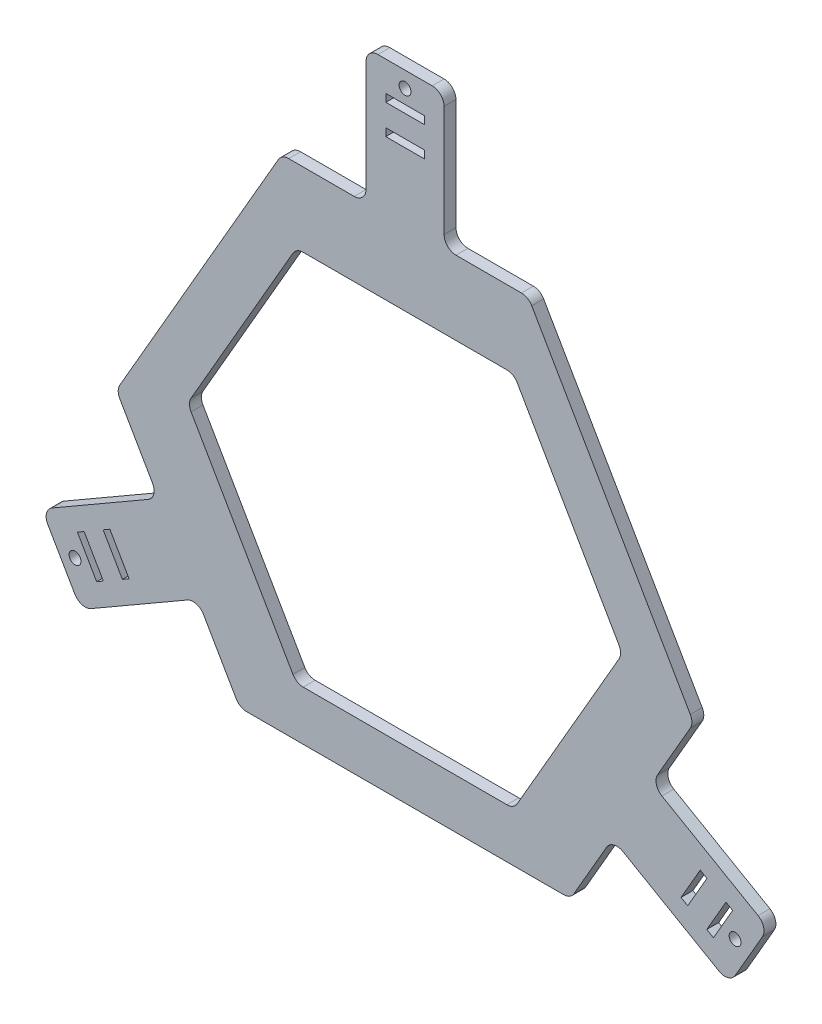
SolidWorks part; units mm, degrees
ref_plane "Спереди" through (0, 0, 0) normal (0, 0, 1) x (1, 0, 0)
ref_plane "Сверху" through (0, 0, 0) normal (0, 1, 0) x (1, 0, 0)
ref_plane "Справа" through (0, 0, 0) normal (1, 0, 0) x (0, 0, -1)
other "Configuration Table"
sketch "Эскиз1" plane through (0, 0, 0) normal (0, 0, 1) x (1, 0, 0)
  line L0 (0, 0) -> (-158.7702, -91.666) construction
  line L4 (-77.8045, -50.5207) -> (-82.6545, -42.1203)
  line L6 (-88.8379, -46.4103) -> (-84.6114, -53.7308)
  line L12 (82.6545, -42.1203) -> (76.1157, -49.5457) construction
  line L13 (-77.8045, -50.5207) -> (-76.1157, -49.5457)
  line L14 (-82.6545, -42.1203) -> (-80.9657, -41.1453)
  line L15 (-76.1157, -49.5457) -> (-80.9657, -41.1453)
  line L16 (-77.8045, -50.5207) -> (-80.9657, -41.1453) construction
  line L17 (-82.6545, -42.1203) -> (-76.1157, -49.5457) construction
  line L26 (-71.3093, -46.7707) -> (-76.1593, -38.3703)
  line L27 (-71.3093, -46.7707) -> (-69.6205, -45.7957)
  line L28 (-76.1593, -38.3703) -> (-74.4705, -37.3953)
  line L29 (-69.6205, -45.7957) -> (-74.4705, -37.3953)
  line L39 (-88.8379, -46.4103) -> (-90.1497, -44.1382)
  line L40 (-89.0516, -40.0402) -> (-64.8029, -26.0402)
  line L41 (-63.7048, -21.9421) -> (-71.9615, -7.641)
  line L43 (-79.2016, -57.1009) -> (-54.9529, -43.1009)
  line L44 (-84.6114, -53.7308) -> (-83.2997, -56.0028)
  line L45 (-50.8548, -44.1989) -> (-42.5981, -58.5)
  line L46 (0, 0) -> (0, 96.141) construction
  line L48 (77.8045, -50.5207) -> (80.9657, -41.1453) construction
  line L49 (50.8548, -44.1989) -> (42.5981, -58.5)
  line L50 (84.6114, -53.7308) -> (83.2997, -56.0028)
  line L51 (79.2016, -57.1009) -> (54.9529, -43.1009)
  line L52 (63.7048, -21.9421) -> (71.9615, -7.641)
  line L53 (89.0516, -40.0402) -> (64.8029, -26.0402)
  line L54 (88.8379, -46.4103) -> (90.1497, -44.1382)
  line L55 (69.6205, -45.7957) -> (74.4705, -37.3953)
  line L56 (76.1593, -38.3703) -> (74.4705, -37.3953)
  line L57 (71.3093, -46.7707) -> (69.6205, -45.7957)
  line L58 (71.3093, -46.7707) -> (76.1593, -38.3703)
  line L59 (76.1157, -49.5457) -> (80.9657, -41.1453)
  line L60 (82.6545, -42.1203) -> (80.9657, -41.1453)
  line L61 (77.8045, -50.5207) -> (76.1157, -49.5457)
  line L62 (88.8379, -46.4103) -> (84.6114, -53.7308)
  line L63 (77.8045, -50.5207) -> (82.6545, -42.1203)
  line L64 (-40, -60) -> (40, -60)
  line L66 (0, 0) -> (86.7247, -50.0705) construction
  line L67 (-4.85, 92.641) -> (4.85, 90.691) construction
  line L68 (4.85, 92.641) -> (-4.85, 90.691) construction
  line L69 (-4.85, 92.641) -> (4.85, 92.641)
  line L70 (4.2265, 100.141) -> (-4.2265, 100.141)
  line L71 (-4.85, 92.641) -> (-4.85, 90.691)
  line L72 (4.85, 92.641) -> (4.85, 90.691)
  line L73 (-4.85, 90.691) -> (4.85, 90.691)
  line L74 (-4.85, 85.141) -> (4.85, 85.141)
  line L75 (-4.85, 85.141) -> (-4.85, 83.191)
  line L76 (4.85, 85.141) -> (4.85, 83.191)
  line L77 (-4.85, 83.191) -> (4.85, 83.191)
  line L78 (4.2265, 100.141) -> (6.85, 100.141)
  line L79 (9.85, 97.141) -> (9.85, 69.141)
  line L80 (12.85, 66.141) -> (29.3634, 66.141)
  line L81 (-9.85, 97.141) -> (-9.85, 69.141)
  line L82 (-4.2265, 100.141) -> (-6.85, 100.141)
  line L83 (-12.85, 66.141) -> (-29.3634, 66.141)
  line L84 (-71.9615, -4.641) -> (-31.9615, 64.641)
  line L85 (31.9615, 64.641) -> (71.9615, -4.641)
  arc A0 (79.2016, -57.1009) -> (83.2997, -56.0028) centre (80.7016, -54.5028) ccw
  circle A1 centre (-83.2606, -48.0705) radius 1.5
  arc A11 (-90.1497, -44.1382) -> (-89.0516, -40.0402) centre (-87.5516, -42.6382) cw
  arc A12 (-71.9615, -7.641) -> (-71.9615, -4.641) centre (-69.3634, -6.141) cw
  arc A13 (-40, -60) -> (-42.5981, -58.5) centre (-40, -57) cw
  arc A14 (-63.7048, -21.9421) -> (-64.8029, -26.0402) centre (-66.3029, -23.4421) cw
  arc A15 (-50.8548, -44.1989) -> (-54.9529, -43.1009) centre (-53.4529, -45.6989) ccw
  arc A16 (-79.2016, -57.1009) -> (-83.2997, -56.0028) centre (-80.7016, -54.5028) cw
  arc A17 (50.8548, -44.1989) -> (54.9529, -43.1009) centre (53.4529, -45.6989) cw
  arc A18 (63.7048, -21.9421) -> (64.8029, -26.0402) centre (66.3029, -23.4421) ccw
  arc A19 (40, -60) -> (42.5981, -58.5) centre (40, -57) ccw
  arc A20 (71.9615, -7.641) -> (71.9615, -4.641) centre (69.3634, -6.141) ccw
  arc A21 (90.1497, -44.1382) -> (89.0516, -40.0402) centre (87.5516, -42.6382) ccw
  circle A22 centre (83.2606, -48.0705) radius 1.5
  circle A23 centre (0, 96.141) radius 1.5
  arc A24 (6.85, 100.141) -> (9.85, 97.141) centre (6.85, 97.141) cw
  arc A25 (29.3634, 66.141) -> (31.9615, 64.641) centre (29.3634, 63.141) cw
  arc A26 (-31.9615, 64.641) -> (-29.3634, 66.141) centre (-29.3634, 63.141) cw
  arc A27 (12.85, 66.141) -> (9.85, 69.141) centre (12.85, 69.141) cw
  arc A28 (-12.85, 66.141) -> (-9.85, 69.141) centre (-12.85, 69.141) ccw
  arc A29 (-9.85, 97.141) -> (-6.85, 100.141) centre (-6.85, 97.141) cw
  circle A30 centre (0, 0) radius 60 construction
  point P4 (-79.3851, -45.833)
  point P9 (-86.7247, -50.0705)
  point P65 (-91.6497, -41.5402)
  point P68 (0, 0)
  point P71 (0, 0)
  point P74 (-62.2048, -24.5402)
  point P77 (-52.3548, -41.6009)
  point P80 (-81.7997, -58.6009)
  point P91 (81.7997, -58.6009)
  point P92 (52.3548, -41.6009)
  point P93 (62.2048, -24.5402)
  point P94 (0, 0)
  point P95 (0, 0)
  point P96 (91.6497, -41.5402)
  point P99 (86.7247, -50.0705)
  point P100 (79.3851, -45.833)
  point P114 (0, 91.666)
  point P115 (0, 100.141)
  point P118 (9.85, 100.141)
  point P119 (0, 0)
  point P120 (0, 0)
  point P121 (9.85, 66.141)
  point P122 (-9.85, 66.141)
  point P123 (-9.85, 100.141)
  dimension "D5" = 3
  dimension "D12" = 8.453
  dimension "D13" = 5
  dimension "D2" = 120
  dimension "D16" = 3
  dimension "D17" = 3
  dimension "D3" = 1.95
  dimension "D4" = 80
  dimension "D6" = 9.7
  dimension "D7" = 4
  dimension "D9" = 3.5
  dimension "D10" = 5.55
  dimension "D11" = 1.95
  dimension "D15" = 34
extrude "Бобышка-Вытянуть3" add sketch "Эскиз1" along normal blind 3
sketch "Эскиз2" plane through (0, 0, 3) normal (0, 0, 1) x (1, 0, 0)
  line L0 (-12.85, 66.141) -> (-29.3634, 66.141) construction
  line L1 (28.2902, -46) -> (53.9823, -1.5)
  line L2 (53.9823, 1.5) -> (28.2902, 46)
  line L3 (25.6921, 47.5) -> (-25.6921, 47.5)
  line L4 (-28.2902, 46) -> (-53.9823, 1.5)
  line L5 (-53.9823, -1.5) -> (-28.2902, -46)
  line L6 (-25.6921, -47.5) -> (25.6921, -47.5)
  circle A0 centre (0, 0) radius 47.5 construction
  arc A1 (-28.2902, 46) -> (-25.6921, 47.5) centre (-25.6921, 44.5) cw
  arc A2 (25.6921, 47.5) -> (28.2902, 46) centre (25.6921, 44.5) cw
  arc A3 (53.9823, 1.5) -> (53.9823, -1.5) centre (51.3842, 0) cw
  arc A4 (28.2902, -46) -> (25.6921, -47.5) centre (25.6921, -44.5) cw
  arc A5 (-28.2902, -46) -> (-25.6921, -47.5) centre (-25.6921, -44.5) ccw
  arc A6 (-53.9823, -1.5) -> (-53.9823, 1.5) centre (-51.3842, 0) cw
  point P11 (54.8483, 0)
  dimension "D1" = 95
  dimension "D2" = 3
extrude "Вырез-Вытянуть1" cut sketch "Эскиз2" against normal blind 10
